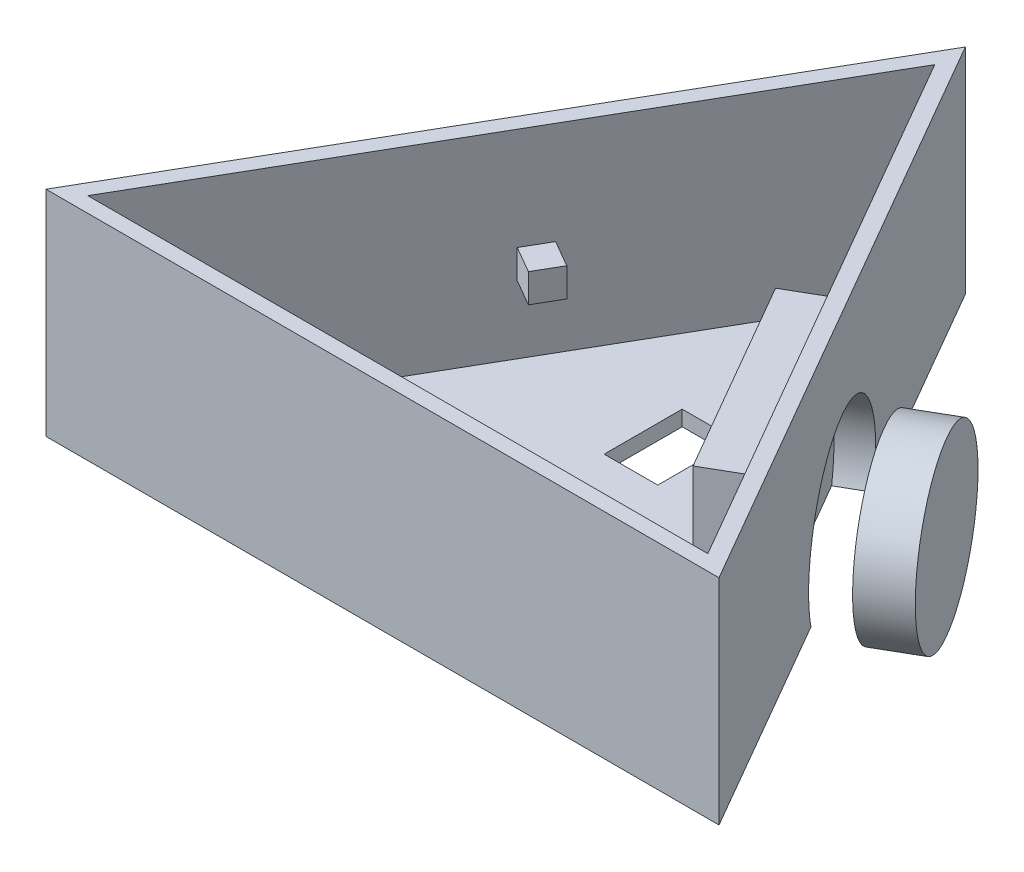
SolidWorks part; units mm, degrees
ref_plane "Front Plane" through (0, 0, 0) normal (0, 0, 1) x (1, 0, 0)
ref_plane "Top Plane" through (0, 0, 0) normal (0, 1, 0) x (1, 0, 0)
ref_plane "Right Plane" through (0, 0, 0) normal (1, 0, 0) x (0, 0, -1)
sketch "Sketch1" plane through (0, 0, 0) normal (0, 1, 0) x (1, 0, 0)
  line L0 (110, 0) -> (-110, 0)
  line L1 (0, -29.4744) -> (0, 190.5256) construction
  line L2 (-110, 0) -> (0, 190.5256)
  line L3 (0, 190.5256) -> (110, 0)
  point P3 (0, 0)
  dimension "D1" = 220
  dimension "D2" = 220
  dimension "D3" = 220
  dimension "D4" = 220
extrude "Boss-Extrude1" add sketch "Sketch1" along normal blind 70
sketch "Sketch2" plane through (0, 70, 0) normal (0, 1, 0) x (1, 0, 0)
  line L9 (-101.3397, 5) -> (101.3397, 5)
  line L10 (101.3397, 5) -> (0, 180.5256)
  line L11 (0, 180.5256) -> (-101.3397, 5)
  line L12 (-101.3397, 5) -> (101.3397, 5)
  line L13 (101.3397, 5) -> (0, 180.5256)
  line L14 (0, 180.5256) -> (-101.3397, 5)
  dimension "D1" = 5
extrude "Cut-Extrude1" cut sketch "Sketch2" against normal blind 65
ref_plane "Plane1" through (91.1603, 0, -52.6314) normal (0.866, 0, -0.5) x (-0.5, 0, -0.866)
sketch "Sketch3" plane through (91.1603, 0, -52.6314) normal (0.866, 0, -0.5) x (-0.5, 0, -0.866)
  line L0 (-55, 70) -> (165, 70) construction
  line L2 (-55, 0) -> (165, 0) construction
  circle A0 centre (55, 11) radius 28
  point P4 (55, 70)
  point P5 (0, 0)
  point P9 (0, 0)
  point P10 (0, 0)
  point P11 (55, 6.6581)
  dimension "D2" = 56
  dimension "D1" = 11
extrude "Boss-Extrude2" add sketch "Sketch3" along normal blind 15 separate body
sketch "Sketch4" plane through (82.5, 0, -47.6314) normal (0.866, 0, -0.5) x (-0.5, 0, -0.866)
  line L0 (55, 11) -> (63.8982, 11) construction
  circle A0 centre (55, 11) radius 2
  dimension "D1" = 4
extrude "Cut-Extrude2" cut sketch "Sketch4" against normal blind 65
sketch "Sketch5" plane through (0, 5, 0) normal (0, 1, 0) x (1, 0, 0)
  line L1 (8.7589, 81.2171) -> (-8.7589, 81.2171)
  line L2 (8.7589, 81.2171) -> (8.7589, 106.7158)
  line L3 (8.7589, 106.7158) -> (-8.7589, 106.7158)
  line L4 (-8.7589, 81.2171) -> (-8.7589, 106.7158)
  line L5 (8.7589, 81.2171) -> (-8.7589, 106.7158) construction
  line L6 (8.7589, 106.7158) -> (-8.7589, 81.2171) construction
  point P0 (0, 93.9664)
extrude "Cut-Extrude3" cut sketch "Sketch5" against normal blind 65
sketch "Sketch6" plane through (-78.1699, 0, -45.1314) normal (0.866, 0, 0.5) x (0.5, 0, -0.866)
  line L1 (65.6036, 27.1074) -> (56.4259, 27.1074)
  line L2 (65.6036, 27.1074) -> (65.6036, 36.5143)
  line L3 (65.6036, 36.5143) -> (56.4259, 36.5143)
  line L4 (56.4259, 27.1074) -> (56.4259, 36.5143)
  line L5 (65.6036, 27.1074) -> (56.4259, 36.5143) construction
  line L6 (65.6036, 36.5143) -> (56.4259, 27.1074) construction
  point P0 (61.0148, 31.8109)
extrude "Boss-Extrude3" add sketch "Sketch6" along normal blind 10
sketch "Sketch8" plane through (0, 5, 0) normal (0, 1, 0) x (1, 0, 0)
  line L0 (34.3253, 121.0724) -> (17.2563, 111.2176)
  line L1 (17.2563, 111.2176) -> (54.1006, 47.4015)
  line L2 (54.1006, 47.4015) -> (71.1695, 57.2563)
  line L3 (71.1695, 57.2563) -> (34.3253, 121.0724)
  line L4 (34.3253, 121.0724) -> (35.2984, 119.866)
  line M7 (101.3397, 5) -> (0, 180.5256)
extrude "Boss-Extrude4" add sketch "Sketch8" along normal offset from surface (45 mm away) 20 contours L1 L2 L0 M7 up to face at (0, 70, -63.5085)
sketch "Sketch7" plane through (82.5, 0, -47.6314) normal (0.866, 0, -0.5) x (-0.5, 0, -0.866)
  circle A2 centre (55, 11) radius 30
  circle A3 centre (55, 11) radius 30
  dimension "D1" = 2
extrude "Cut-Extrude4" cut sketch "Sketch7" against normal blind 10
